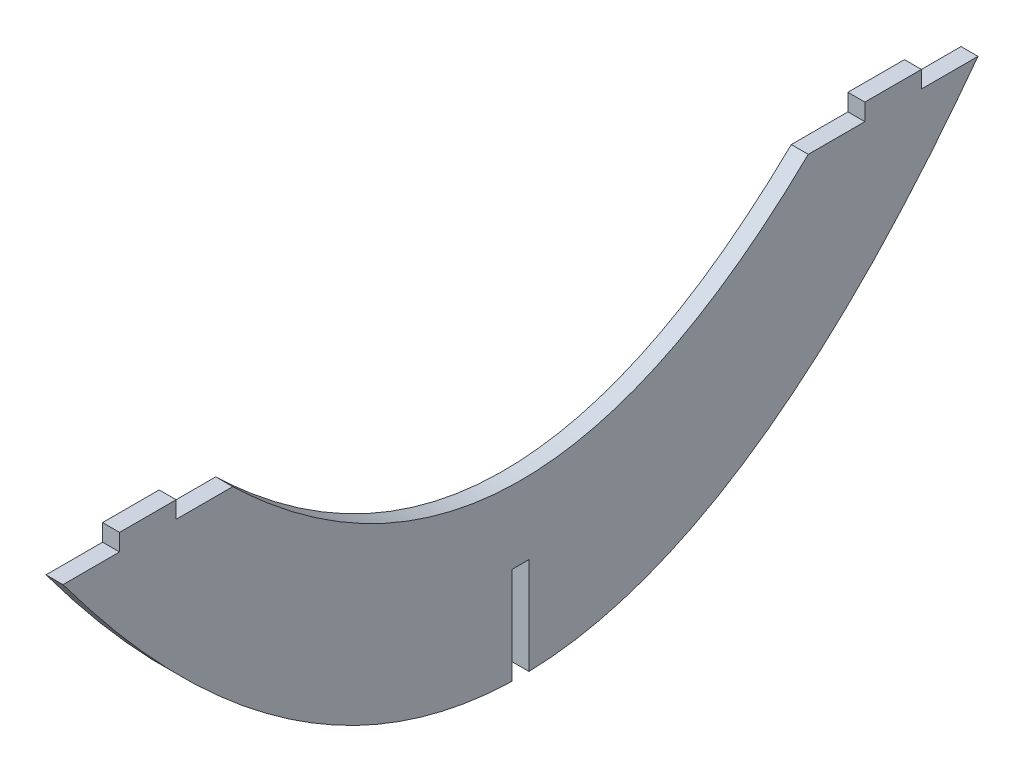
SolidWorks part; units mm, degrees
ref_plane "前视基准面" through (0, 0, 0) normal (0, 0, 1) x (1, 0, 0)
ref_plane "上视基准面" through (0, 0, 0) normal (0, 1, 0) x (1, 0, 0)
ref_plane "右视基准面" through (0, 0, 0) normal (1, 0, 0) x (0, 0, -1)
sketch "草图1" plane through (0, 0, 0) normal (1, 0, 0) x (0, 0, -1)
  line L0 (-80.8728, 119.9978) -> (-50.8705, 119.9978)
  line L1 (50.8705, 119.9978) -> (80.8728, 119.9978)
  spline S0 degree 2 poles (-92.406, 136.651) (0, -5.6577) (92.406, 136.651) knots 0 0 0 1 1 1 construction
  spline S1 degree 2 poles (-80.8728, 119.9978) (0, 10.9954) (80.8728, 119.9978) knots 0.062405 0.062405 0.062405 0.937595 0.937595 0.937595
  spline S2 degree 2 poles (-91.9481, 175.5428) (0, 15.4504) (91.9481, 175.5428) knots 0 0 0 1 1 1 construction
  spline S3 degree 2 poles (-50.8705, 119.9978) (0, 70.9954) (50.8705, 119.9978) knots 0.223374 0.223374 0.223374 0.776626 0.776626 0.776626
extrude "凸台-拉伸1" add sketch "草图1" along normal blind 3
sketch "草图2" plane through (0, 119.9978, 0) normal (0, 1, 0) x (1, 0, 0)
  line L0 (0, -80.8728) -> (3, -50.8705)
  line L1 (3, 50.8705) -> (0, 80.8728)
  line L2 (3, 80.8728) -> (3, 50.8705) construction
  line L3 (0, 60.8716) -> (3, 60.8716)
  line L4 (0, 60.8716) -> (0, 70.8716)
  line L5 (0, 70.8716) -> (3, 70.8716)
  line L6 (3, 60.8716) -> (3, 70.8716)
  line L7 (0, 60.8716) -> (3, 70.8716) construction
  line L8 (0, 70.8716) -> (3, 60.8716) construction
  line L9 (0, -50.8705) -> (0, -80.8728) construction
  line L10 (3, -70.8716) -> (0, -70.8716)
  line L11 (3, -70.8716) -> (3, -60.8716)
  line L12 (3, -60.8716) -> (0, -60.8716)
  line L13 (0, -70.8716) -> (0, -60.8716)
  line L14 (3, -70.8716) -> (0, -60.8716) construction
  line L15 (3, -60.8716) -> (0, -70.8716) construction
  point P8 (1.5, 65.8716)
  point P15 (1.5, -65.8716)
  line M2 (0, -50.8705) -> (0, -80.8728)
  line M4 (3, -80.8728) -> (3, -50.8705)
extrude "凸台-拉伸2" add sketch "草图2" along normal blind 3 contours L5 L4 L3 L1 | L3 L6 L5 L1 | L0 L12 L10 M2 | L12 L0 L10 M4
sketch "草图3" plane through (0, 0, 0) normal (-1, 0, 0) x (0, 0, 1)
  line L0 (-1.5, 100.8903) -> (-1.5, 82.6427) construction
  line L1 (-1.5, 100.8903) -> (-1.5, 82.6427)
  line L3 (-1.5, 82.6427) -> (1.5, 82.6427)
  line L4 (-1.5, 82.6427) -> (-1.5, 59.2323)
  line L5 (-1.5, 59.2323) -> (1.5, 59.2323)
  line L6 (1.5, 82.6427) -> (1.5, 59.2323)
  spline M7 degree 2 poles (-80.8728, 119.9978) (0, 10.9954) (80.8728, 119.9978) knots 0.062405 0.062405 0.062405 0.937595 0.937595 0.937595
extrude "切除-拉伸1" cut sketch "草图3" against normal through all contours L6 L3 L4 M7
